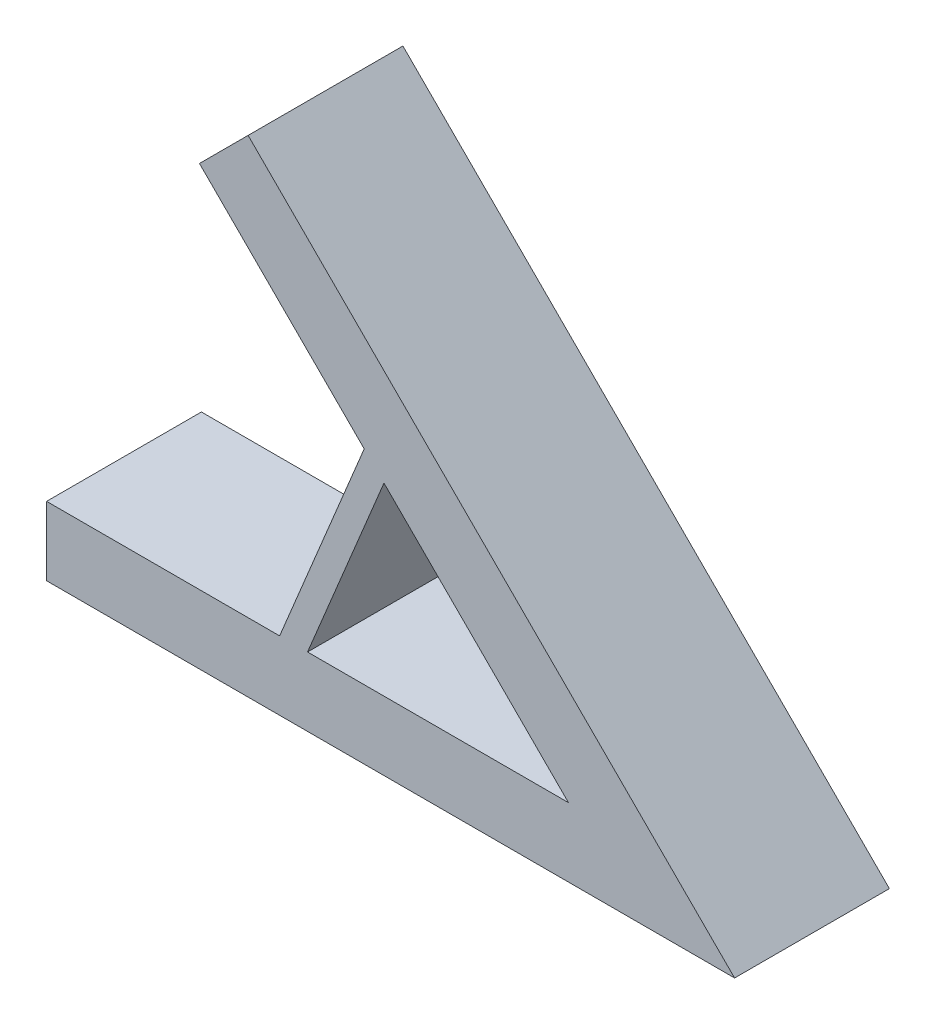
SolidWorks part; units mm, degrees
ref_plane "前视基准面" through (0, 0, 0) normal (0, 0, 1) x (1, 0, 0)
ref_plane "上视基准面" through (0, 0, 0) normal (0, 1, 0) x (1, 0, 0)
ref_plane "右视基准面" through (0, 0, 0) normal (1, 0, 0) x (0, 0, -1)
sketch "草图1" plane through (0, 0, 0) normal (0, 0, 1) x (1, 0, 0)
  line L0 (-80, 0) -> (0, 0)
  line L1 (0, 0) -> (-56.5685, 56.5685)
  line L2 (-56.5685, 56.5685) -> (-62.2254, 50.9117)
  line L3 (-62.2254, 50.9117) -> (-19.3137, 8)
  line L4 (-19.3137, 8) -> (-80, 8)
  line L5 (-80, 8) -> (-80, 0)
  line L6 (-49.6569, 8) -> (-40.7696, 29.4558)
  line L7 (-40.7696, 29.4558) -> (-43.0657, 31.7519)
  line L8 (-43.0657, 31.7519) -> (-52.904, 8)
  line L9 (-52.904, 8) -> (-49.6569, 8)
  dimension "D1" = 45
  dimension "D2" = 80
  dimension "D3" = 80
  dimension "D4" = 8
  dimension "D5" = 8
  dimension "D6" = 3
extrude "凸台-拉伸1" add sketch "草图1" along normal blind 18 contours L4 L5 L0 L1 L2 L3 | L3 L8 L4 L6
